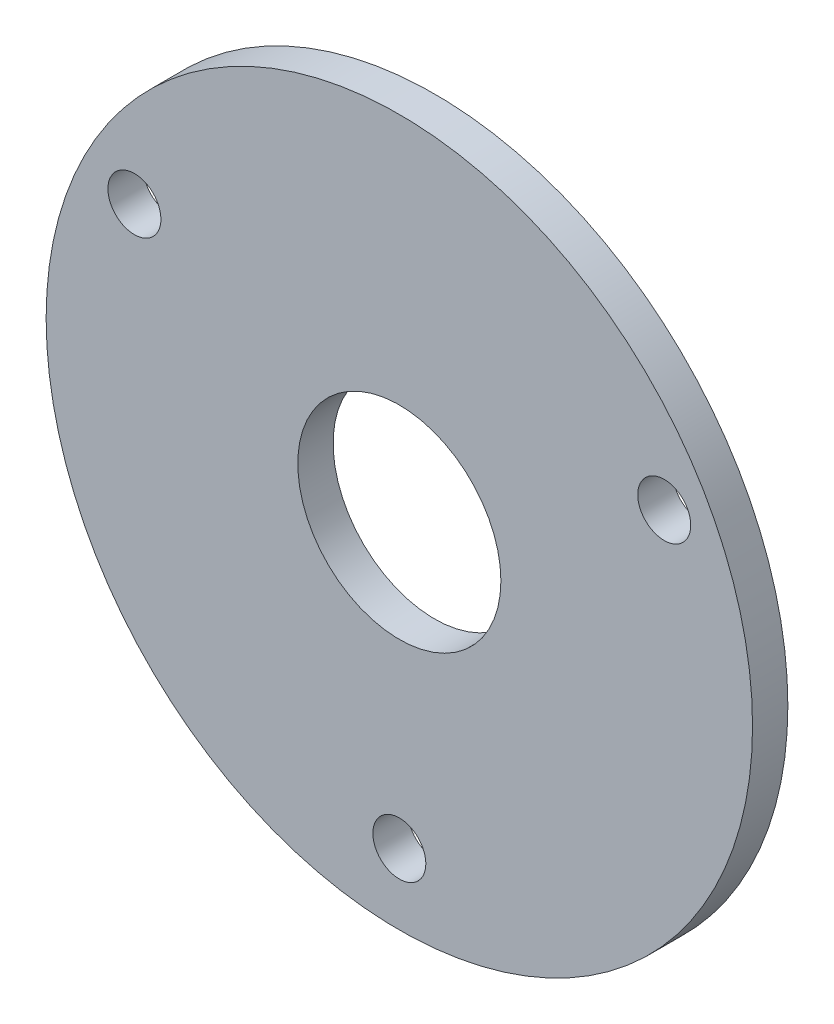
SolidWorks part; units mm, degrees
material "PETG"
ref_plane "Alzado" through (0, 0, 0) normal (0, 0, 1) x (1, 0, 0)
ref_plane "Planta" through (0, 0, 0) normal (0, 1, 0) x (1, 0, 0)
ref_plane "Vista lateral" through (0, 0, 0) normal (1, 0, 0) x (0, 0, -1)
sketch "Croquis1" plane through (0, 0, 0) normal (0, 0, 1) x (1, 0, 0)
  line L0 (0, 0) -> (0, -16) construction
  circle A1 centre (0, 0) radius 20
  circle A2 centre (15, 8.1) radius 1.5
  circle A3 centre (0, -16) radius 1.5
  circle A4 centre (-15, 8.1) radius 1.5
  dimension "D1" = 8.1
  dimension "D2" = 40
  dimension "D3" = 3
  dimension "D4" = 3
  dimension "D5" = 15
  dimension "D6" = 16
extrude "Saliente-Extruir1" add sketch "Croquis1" along normal blind 2
sketch "Croquis2" plane through (0, 0, 2) normal (0, 0, 1) x (1, 0, 0)
  circle A0 centre (0, 0) radius 5.75
  dimension "D1" = 11.5
extrude "Cortar-Extruir1" cut sketch "Croquis2" against normal blind 10
